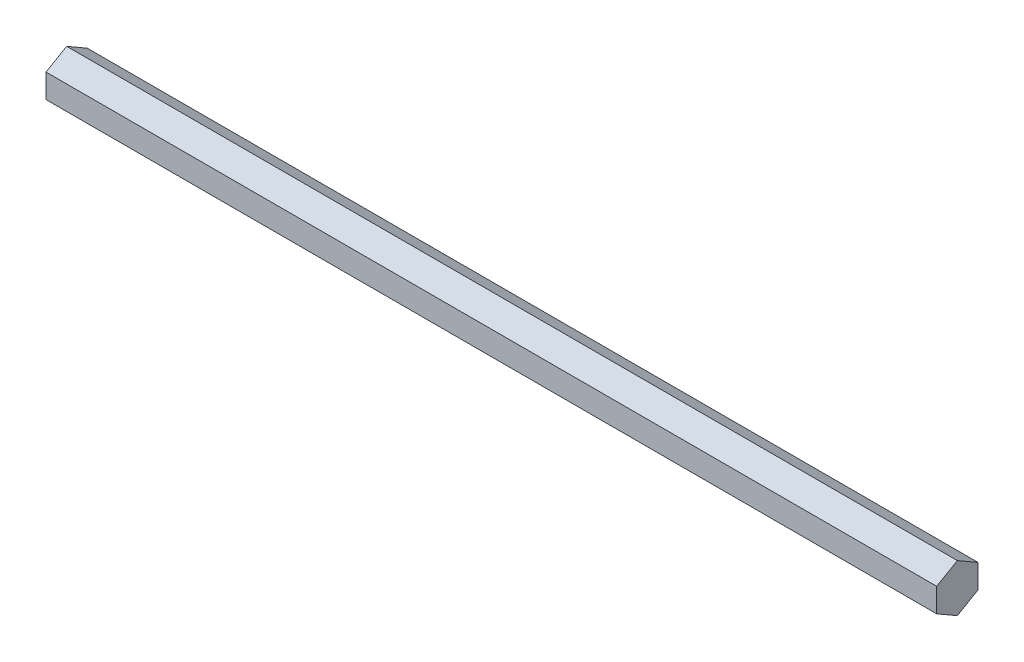
SolidWorks part; units mm, degrees
ref_plane "Front Plane" through (0, 0, 0) normal (0, 0, 1) x (1, 0, 0)
ref_plane "Top Plane" through (0, 0, 0) normal (0, 1, 0) x (1, 0, 0)
ref_plane "Right Plane" through (0, 0, 0) normal (1, 0, 0) x (0, 0, -1)
sketch "Hex Profile" plane through (0, 0, 0) normal (1, 0, 0) x (0, 0, -1)
  line L1 (4.1244, -2.3813) -> (4.1244, 2.3813)
  line L2 (4.1244, 2.3813) -> (0, 4.7625)
  line L3 (0, 4.7625) -> (-4.1244, 2.3813)
  line L4 (-4.1244, 2.3813) -> (-4.1244, -2.3813)
  line L5 (-4.1244, -2.3813) -> (0, -4.7625)
  line L6 (0, -4.7625) -> (4.1244, -2.3813)
  circle A0 centre (0, 0) radius 4.7625 construction
  dimension "D1" = 9.525
extrude "Axle" add sketch "Hex Profile" along normal blind 177.8
sketch "Motor Shaft Profile" plane through (0, 0, 0) normal (-1, 0, 0) x (0, 0, 1)
  line L0 (-1.6695, 2.4892) -> (1.6695, 2.4892)
  line L1 (0, -2.9972) -> (0, 2.4892) construction
  arc A0 (-1.6695, 2.4892) -> (1.6695, 2.4892) centre (0, 0) ccw
  arc A1 (1.6695, 2.4892) -> (-1.6695, 2.4892) centre (0, 0) ccw construction
  dimension "D1" = 5.9944
  dimension "D2" = 5.4864
extrude "Drive  Slot" cut sketch "Motor Shaft Profile" against normal blind 13.97
